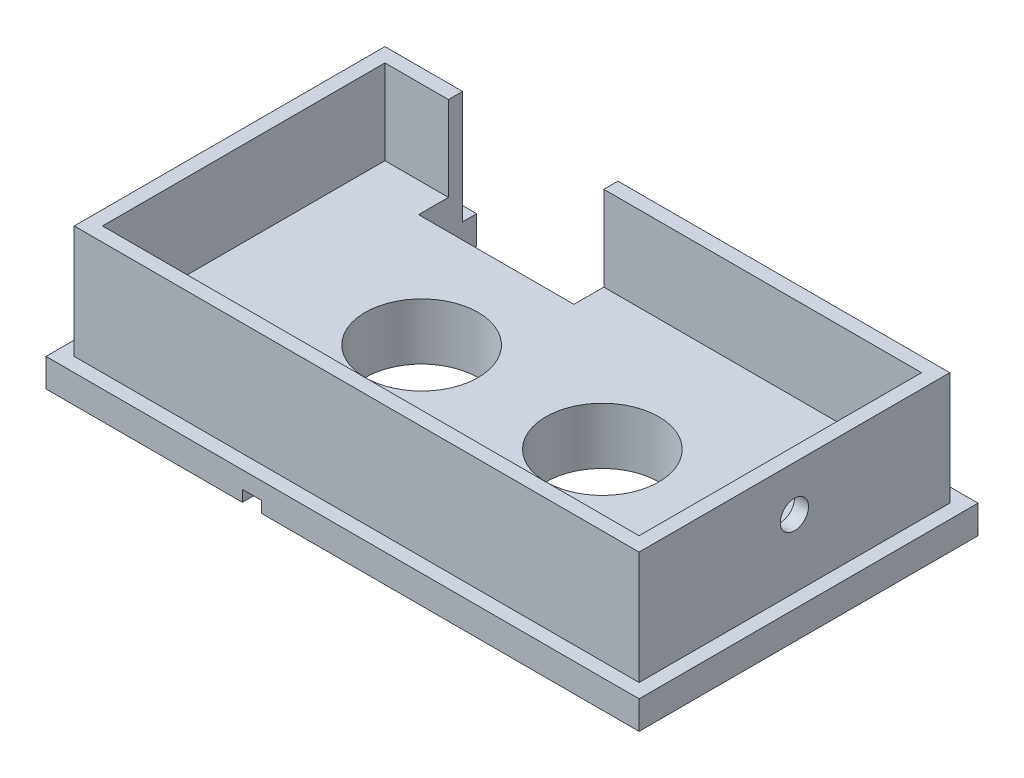
SolidWorks part; units mm, degrees
ref_plane "Front Plane" through (0, 0, 0) normal (0, 0, 1) x (1, 0, 0)
ref_plane "Top Plane" through (0, 0, 0) normal (0, 1, 0) x (1, 0, 0)
ref_plane "Right Plane" through (0, 0, 0) normal (1, 0, 0) x (0, 0, -1)
sketch "Sketch1" plane through (0, 0, 0) normal (0, 1, 0) x (1, 0, 0)
  line L1 (0, 0) -> (42, 0)
  line L2 (0, 0) -> (0, 24)
  line L3 (0, 24) -> (42, 24)
  line L4 (42, 0) -> (42, 24)
extrude "Boss-Extrude1" add sketch "Sketch1" along normal blind 2
sketch3d "3DSketch1"
  line L0 (1, 2, -1) -> (41, 2, -1)
  line L1 (41, 2, -1) -> (41, 2, -23)
  line L2 (41, 2, -23) -> (1, 2, -23)
  line L3 (1, 2, -23) -> (1, 2, -1)
  line L4 (1, 2, -1) -> (41, 2, -1)
  line L5 (41, 2, -1) -> (41, 2, -23)
  line L6 (41, 2, -23) -> (1, 2, -23)
  line L7 (1, 2, -23) -> (1, 2, -1)
  dimension "D1" = 1
extrude "Boss-Extrude2" add sketch "3DSketch1" along direction (0, -1, 0) on the side against the normal blind 8 contours L4 L5 L6 L7
sketch3d "3DSketch2"
  line L0 (2, 10, -2) -> (40, 10, -2)
  line L1 (40, 10, -2) -> (40, 10, -22)
  line L2 (40, 10, -22) -> (2, 10, -22)
  line L3 (2, 10, -22) -> (2, 10, -2)
  line L4 (2, 10, -2) -> (40, 10, -2)
  line L5 (40, 10, -2) -> (40, 10, -22)
  line L6 (40, 10, -22) -> (2, 10, -22)
  line L7 (2, 10, -22) -> (2, 10, -2)
  dimension "D1" = 1
extrude "Cut-Extrude1" cut sketch "3DSketch2" along direction (0, -1, 0) on the side of the normal blind 6
sketch "Sketch2" plane through (0, 0, 0) normal (0, -1, 0) x (1, 0, 0)
  line L0 (42, -12) -> (0, -12) construction
  line L1 (42, 0) -> (42, -24) construction
  line L2 (0, -24) -> (0, 0) construction
  line L3 (21, -24) -> (21, 0) construction
  line L4 (42, -24) -> (0, -24) construction
  line L5 (0, 0) -> (42, 0) construction
  circle A0 centre (27.4, -12) radius 4
  circle A1 centre (14.6, -12) radius 4
  dimension "D1" = 12.8
extrude "Cut-Extrude2" cut sketch "Sketch2" against normal up to next
sketch "Sketch3" plane through (0, 0, 0) normal (0, -1, 0) x (1, 0, 0)
  text T0 "   +  -" font "Clarendon Blk BT" height 7
extrude "Cut-Extrude3" cut sketch "Sketch3" against normal blind 0.8
sketch "Sketch4" plane through (0, 0, 0) normal (0, -1, 0) x (1, 0, 0)
  line L0 (42, -24) -> (0, -24) construction
  line L1 (6.5, -24) -> (17.5, -24)
  line L2 (6.5, -24) -> (6.5, -19.8855)
  line L3 (6.5, -19.8855) -> (17.5, -19.8855)
  line L4 (17.5, -24) -> (17.5, -19.8855)
  dimension "D1" = 11
  dimension "D2" = 4.1145
  dimension "D3" = 6.5
extrude "Cut-Extrude4" cut sketch "Sketch4" against normal up to next contours L2 L1 L4 L3
sketch "Sketch5" plane through (41, 0, 0) normal (1, 0, 0) x (0, 0, -1)
  line L0 (12, 10) -> (12, 2) construction
  line L1 (1, 10) -> (23, 10) construction
  line L2 (1, 2) -> (23, 2) construction
  circle A0 centre (12, 6.8) radius 1
  dimension "D1" = 3.2
extrude "Cut-Extrude5" cut sketch "Sketch5" against normal up to next
